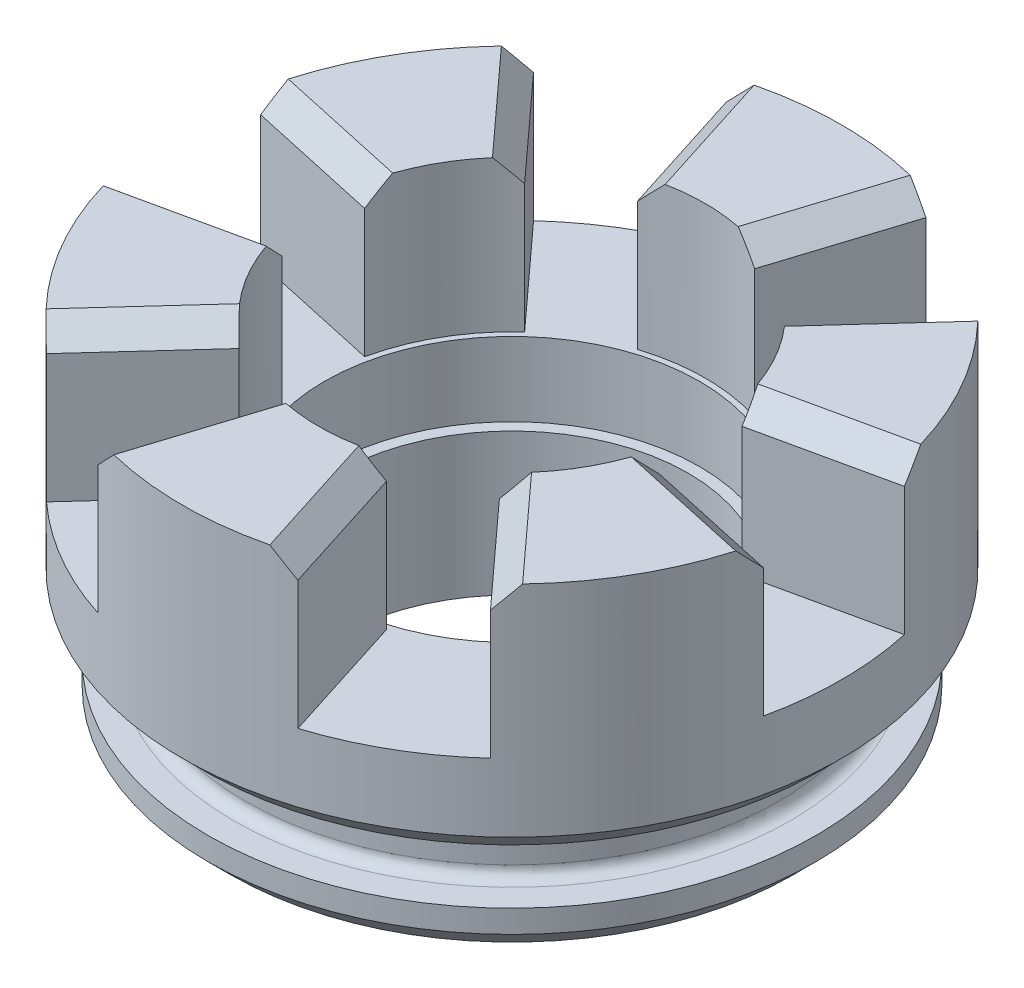
SolidWorks part; units mm, degrees
ref_plane "Front Plane" through (0, 0, 0) normal (0, 0, 1) x (1, 0, 0)
ref_plane "Top Plane" through (0, 0, 0) normal (0, 1, 0) x (1, 0, 0)
ref_plane "Right Plane" through (0, 0, 0) normal (1, 0, 0) x (0, 0, -1)
sketch "Sketch1" plane through (0, 0, 0) normal (0, 0, 1) x (1, 0, 0)
  line L0 (0, 0) -> (-29, 0) construction
  line L1 (-16.5, 0) -> (-29, 0)
  line L2 (-29, 0) -> (-29, -8)
  line L3 (-29, -8) -> (-23.5, -8)
  line L4 (-23.5, -8) -> (-23.5, -13)
  line L5 (-23.5, -13) -> (-26.75, -13)
  line L6 (-26.75, -13) -> (-26.75, -17)
  line L7 (-26.75, -17) -> (-20.5, -17)
  line L8 (-20.5, -17) -> (-20.5, -19)
  line L9 (-20.5, -19) -> (-15.5, -19)
  line L10 (-15.5, -19) -> (-15.5, -6.5)
  line L11 (-15.5, -6.5) -> (-16.5, -6.5)
  line L12 (-16.5, -6.5) -> (-16.5, 0)
  line L13 (0, 0) -> (0, -21.4987) construction
  dimension "D1" = 12.5
  dimension "D2" = 8
  dimension "D3" = 5.5
  dimension "D4" = 16.5
  dimension "D5" = 5
  dimension "D6" = 4
  dimension "D7" = 2
  dimension "D8" = 5
  dimension "D9" = 6.5
  dimension "D10" = 15.5
  dimension "D11" = 6.25
revolve "Revolve1" add sketch "Sketch1" angle 360 about L13
sketch "Sketch2" plane through (0, 0, 0) normal (0, 1, 0) x (1, 0, 0)
  line L0 (0, 17) -> (0, 29) construction
  line L1 (5.1544, 16.1997) -> (8.7928, 27.6349)
  line L2 (-5.1544, 16.1997) -> (-8.7928, 27.6349)
  arc A0 (5.1544, 16.1997) -> (-5.1544, 16.1997) centre (0, 0) ccw
  circle A1 centre (0, 0) radius 29 construction
  arc A2 (8.7928, 27.6349) -> (-8.7928, 27.6349) centre (0, 0) ccw
  dimension "D1" = 34
  dimension "D2" = 35.3
extrude "Boss-Extrude1" add sketch "Sketch2" along normal blind 13.3
chamfer "Chamfer1" distance 2 angle 45 2 edges at (-6.9736, 13.3, -21.9173) (6.9736, 13.3, -21.9173)
pattern_circular "CirPattern1" count 6 over 360 about axis through (0, 0, 0) along (0, 1, 0) of "Boss-Extrude1", "Chamfer1"
chamfer "Chamfer2" distance 2 angle 45 2 edges at (0, -17, 26.75) (0, -8, 29)
fillet "Fillet1" radius 1 2 edges at (0, -13, 23.5) (0, -8, 23.5)
equation "\"A\"= 12.5mm"
equation "\"D1@Sketch1\"=\"A\""
equation "\"D2@Sketch1\"=\"A\"*(8/12.5)"
equation "\"D3@Sketch1\"=\"A\"*(5.5/12.5)"
equation "\"D4@Sketch1\"=\"A\"*(16.5/12.5)"
equation "\"D5@Sketch1\"=\"A\"*(5/12.5)"
equation "\"D6@Sketch1\"=\"A\"*(4/12.5)"
equation "\"D7@Sketch1\"=\"A\"*(2/12.5)"
equation "\"D8@Sketch1\"=\"A\"*(5/12.5)"
equation "\"D9@Sketch1\"=\"A\"*(6.5/12.5)"
equation "\"D10@Sketch1\"=\"A\"*(15.5/12.5)"
equation "\"D11@Sketch1\"=\"A\"*(6.25/12.5)"
equation "\"D1@Sketch2\"=\"A\"*(34/12.5)"
equation "\"D1@Boss-Extrude1\"=\"A\"*(13.3/12.5)"
equation "\"D1@Chamfer1\"=\"A\"*(2/12.5)"
equation "\"D1@Chamfer2\"=\"A\"*(2/12.5)"
equation "\"D1@Fillet1\"=\"A\"*(1/12.5)"
